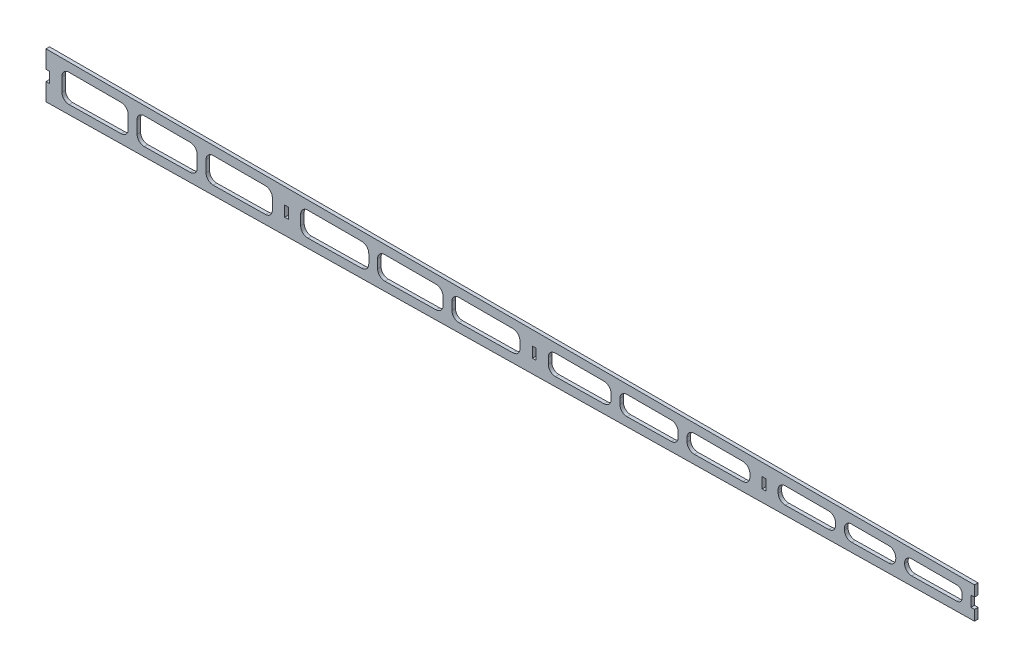
SolidWorks part; units mm, degrees
ref_plane "前视基准面" through (0, 0, 0) normal (0, 0, 1) x (1, 0, 0)
ref_plane "上视基准面" through (0, 0, 0) normal (0, 1, 0) x (1, 0, 0)
ref_plane "右视基准面" through (0, 0, 0) normal (1, 0, 0) x (0, 0, -1)
sketch "草图1" plane through (0, 0, 0) normal (0, 0, 1) x (1, 0, 0)
  line L0 (529.4858, 31.7398) -> (4.4858, 31.7398)
  line L1 (139.4858, 22.7398) -> (141.4858, 22.7398)
  line L2 (141.4858, 22.7398) -> (141.4858, 16.7398)
  line L3 (141.4858, 16.7398) -> (139.4858, 16.7398)
  line L4 (139.4858, 16.7398) -> (139.4858, 22.7398)
  line L5 (279.4858, 23.7398) -> (281.4858, 23.7398)
  line L6 (281.4858, 23.7398) -> (281.4858, 17.7398)
  line L7 (281.4858, 17.7398) -> (279.4858, 17.7398)
  line L8 (279.4858, 17.7398) -> (279.4858, 23.7398)
  line L9 (409.4858, 24.7398) -> (411.4858, 24.7398)
  line L10 (411.4858, 24.7398) -> (411.4858, 18.7398)
  line L11 (411.4858, 18.7398) -> (409.4858, 18.7398)
  line L12 (409.4858, 18.7398) -> (409.4858, 24.7398)
  line L13 (4.4858, 31.7398) -> (4.4858, 21.7398)
  line L14 (4.4858, 21.7398) -> (6.4858, 21.7398)
  line L15 (6.4858, 21.7398) -> (6.4858, 15.7398)
  line L16 (6.4858, 15.7398) -> (4.4858, 15.7398)
  line L17 (4.4858, 15.7398) -> (4.4858, 5.7701)
  line L18 (529.4858, 31.7398) -> (529.4858, 25.7398)
  line L19 (529.4858, 25.7398) -> (527.4858, 25.7398)
  line L20 (527.4858, 25.7398) -> (527.4858, 19.7398)
  line L21 (527.4858, 19.7398) -> (529.4858, 19.7398)
  line L22 (529.4858, 19.7398) -> (529.4858, 13.9388)
  line L23 (529.4858, 13.9388) -> (4.4858, 5.7701)
  line L24 (13.4858, 22.7398) -> (13.4858, 14.9734)
  line L25 (17.5481, 10.9739) -> (47.0481, 11.4329)
  line L26 (50.9858, 15.4324) -> (50.9858, 22.7398)
  line L27 (46.9858, 26.7398) -> (17.4858, 26.7398)
  line L28 (55.9858, 22.7398) -> (55.9858, 15.6347)
  line L29 (60.0481, 11.6352) -> (86.0481, 12.0397)
  line L30 (89.9858, 16.0393) -> (89.9858, 22.7398)
  line L31 (85.9858, 26.7398) -> (59.9858, 26.7398)
  line L32 (94.9858, 22.7398) -> (94.9858, 16.2415)
  line L33 (99.0481, 12.242) -> (128.5481, 12.701)
  line L34 (132.4858, 16.7005) -> (132.4858, 22.7398)
  line L35 (128.4858, 26.7398) -> (98.9858, 26.7398)
  line L36 (148.4858, 22.7398) -> (148.4858, 17.074)
  line L37 (152.5481, 13.0745) -> (183.0481, 13.549)
  line L38 (186.9858, 17.5485) -> (186.9858, 22.7398)
  line L39 (182.9858, 26.7398) -> (152.4858, 26.7398)
  line L40 (191.9858, 22.7398) -> (191.9858, 17.7508)
  line L41 (196.0481, 13.7513) -> (225.0481, 14.2025)
  line L42 (228.9858, 18.202) -> (228.9858, 22.7398)
  line L43 (224.9858, 26.7398) -> (195.9858, 26.7398)
  line L44 (233.9858, 22.7398) -> (233.9858, 18.4043)
  line L45 (238.0481, 14.4048) -> (268.5481, 14.8794)
  line L46 (272.4858, 18.8789) -> (272.4858, 22.7398)
  line L47 (268.4858, 26.7398) -> (237.9858, 26.7398)
  line L48 (288.4858, 22.7398) -> (288.4858, 19.2523)
  line L49 (292.5481, 15.2528) -> (320.0481, 15.6807)
  line L50 (323.9858, 19.6802) -> (323.9858, 22.7398)
  line L51 (319.9858, 26.7398) -> (292.4858, 26.7398)
  line L52 (328.9858, 22.7398) -> (328.9858, 19.8825)
  line L53 (333.0481, 15.8829) -> (358.0481, 16.2719)
  line L54 (361.9858, 20.2714) -> (361.9858, 22.7398)
  line L55 (357.9858, 26.7398) -> (332.9858, 26.7398)
  line L56 (366.9858, 22.7398) -> (366.9858, 20.4737)
  line L57 (371.0481, 16.4742) -> (398.5481, 16.9021)
  line L58 (402.4858, 20.9016) -> (402.4858, 22.7398)
  line L59 (398.4858, 26.7398) -> (370.9858, 26.7398)
  line L60 (418.4858, 22.7398) -> (418.4858, 21.275)
  line L61 (422.5481, 17.2755) -> (447.0481, 17.6567)
  line L62 (450.9858, 21.6562) -> (450.9858, 22.7398)
  line L63 (446.9858, 26.7398) -> (422.4858, 26.7398)
  line L64 (455.9858, 22.7398) -> (455.9858, 21.8585)
  line L65 (460.0481, 17.859) -> (481.0481, 18.1858)
  line L66 (484.9858, 22.1853) -> (484.9858, 22.7398)
  line L67 (480.9858, 26.7398) -> (459.9858, 26.7398)
  line L68 (489.9858, 22.7398) -> (489.9858, 22.3875)
  line L69 (494.0481, 18.388) -> (519.5325, 18.7845)
  line L70 (522.4858, 21.7842) -> (522.4858, 23.7398)
  line L71 (519.4858, 26.7398) -> (493.9858, 26.7398)
  arc A0 (17.4858, 26.7398) -> (13.4858, 22.7398) centre (17.4858, 22.7398) ccw
  arc A1 (47.0481, 11.4329) -> (50.9858, 15.4324) centre (46.9858, 15.4324) ccw
  arc A2 (13.4858, 14.9734) -> (17.5481, 10.9739) centre (17.4858, 14.9734) ccw
  arc A3 (50.9858, 22.7398) -> (46.9858, 26.7398) centre (46.9858, 22.7398) ccw
  arc A4 (59.9858, 26.7398) -> (55.9858, 22.7398) centre (59.9858, 22.7398) ccw
  arc A5 (86.0481, 12.0397) -> (89.9858, 16.0393) centre (85.9858, 16.0393) ccw
  arc A6 (55.9858, 15.6347) -> (60.0481, 11.6352) centre (59.9858, 15.6347) ccw
  arc A7 (89.9858, 22.7398) -> (85.9858, 26.7398) centre (85.9858, 22.7398) ccw
  arc A8 (98.9858, 26.7398) -> (94.9858, 22.7398) centre (98.9858, 22.7398) ccw
  arc A9 (128.5481, 12.701) -> (132.4858, 16.7005) centre (128.4858, 16.7005) ccw
  arc A10 (94.9858, 16.2415) -> (99.0481, 12.242) centre (98.9858, 16.2415) ccw
  arc A11 (132.4858, 22.7398) -> (128.4858, 26.7398) centre (128.4858, 22.7398) ccw
  arc A12 (152.4858, 26.7398) -> (148.4858, 22.7398) centre (152.4858, 22.7398) ccw
  arc A13 (183.0481, 13.549) -> (186.9858, 17.5485) centre (182.9858, 17.5485) ccw
  arc A14 (148.4858, 17.074) -> (152.5481, 13.0745) centre (152.4858, 17.074) ccw
  arc A15 (186.9858, 22.7398) -> (182.9858, 26.7398) centre (182.9858, 22.7398) ccw
  arc A16 (195.9858, 26.7398) -> (191.9858, 22.7398) centre (195.9858, 22.7398) ccw
  arc A17 (191.9858, 17.7508) -> (196.0481, 13.7513) centre (195.9858, 17.7508) ccw
  arc A18 (225.0481, 14.2025) -> (228.9858, 18.202) centre (224.9858, 18.202) ccw
  arc A19 (228.9858, 22.7398) -> (224.9858, 26.7398) centre (224.9858, 22.7398) ccw
  arc A20 (237.9858, 26.7398) -> (233.9858, 22.7398) centre (237.9858, 22.7398) ccw
  arc A21 (268.5481, 14.8794) -> (272.4858, 18.8789) centre (268.4858, 18.8789) ccw
  arc A22 (233.9858, 18.4043) -> (238.0481, 14.4048) centre (237.9858, 18.4043) ccw
  arc A23 (272.4858, 22.7398) -> (268.4858, 26.7398) centre (268.4858, 22.7398) ccw
  arc A24 (292.4858, 26.7398) -> (288.4858, 22.7398) centre (292.4858, 22.7398) ccw
  arc A25 (288.4858, 19.2523) -> (292.5481, 15.2528) centre (292.4858, 19.2523) ccw
  arc A26 (320.0481, 15.6807) -> (323.9858, 19.6802) centre (319.9858, 19.6802) ccw
  arc A27 (323.9858, 22.7398) -> (319.9858, 26.7398) centre (319.9858, 22.7398) ccw
  arc A28 (332.9858, 26.7398) -> (328.9858, 22.7398) centre (332.9858, 22.7398) ccw
  arc A29 (358.0481, 16.2719) -> (361.9858, 20.2714) centre (357.9858, 20.2714) ccw
  arc A30 (328.9858, 19.8825) -> (333.0481, 15.8829) centre (332.9858, 19.8825) ccw
  arc A31 (361.9858, 22.7398) -> (357.9858, 26.7398) centre (357.9858, 22.7398) ccw
  arc A32 (370.9858, 26.7398) -> (366.9858, 22.7398) centre (370.9858, 22.7398) ccw
  arc A33 (398.5481, 16.9021) -> (402.4858, 20.9016) centre (398.4858, 20.9016) ccw
  arc A34 (366.9858, 20.4737) -> (371.0481, 16.4742) centre (370.9858, 20.4737) ccw
  arc A35 (402.4858, 22.7398) -> (398.4858, 26.7398) centre (398.4858, 22.7398) ccw
  arc A36 (422.4858, 26.7398) -> (418.4858, 22.7398) centre (422.4858, 22.7398) ccw
  arc A37 (418.4858, 21.275) -> (422.5481, 17.2755) centre (422.4858, 21.275) ccw
  arc A38 (447.0481, 17.6567) -> (450.9858, 21.6562) centre (446.9858, 21.6562) ccw
  arc A39 (450.9858, 22.7398) -> (446.9858, 26.7398) centre (446.9858, 22.7398) ccw
  arc A40 (459.9858, 26.7398) -> (455.9858, 22.7398) centre (459.9858, 22.7398) ccw
  arc A41 (481.0481, 18.1858) -> (484.9858, 22.1853) centre (480.9858, 22.1853) ccw
  arc A42 (455.9858, 21.8585) -> (460.0481, 17.859) centre (459.9858, 21.8585) ccw
  arc A43 (484.9858, 22.7398) -> (480.9858, 26.7398) centre (480.9858, 22.7398) ccw
  arc A44 (493.9858, 26.7398) -> (489.9858, 22.7398) centre (493.9858, 22.7398) ccw
  arc A45 (519.5325, 18.7845) -> (522.4858, 21.7842) centre (519.4858, 21.7842) ccw
  arc A46 (489.9858, 22.3875) -> (494.0481, 18.388) centre (493.9858, 22.3875) ccw
  arc A47 (522.4858, 23.7398) -> (519.4858, 26.7398) centre (519.4858, 23.7398) ccw
extrude "凸台-拉伸1" add sketch "草图1" along normal blind 2
